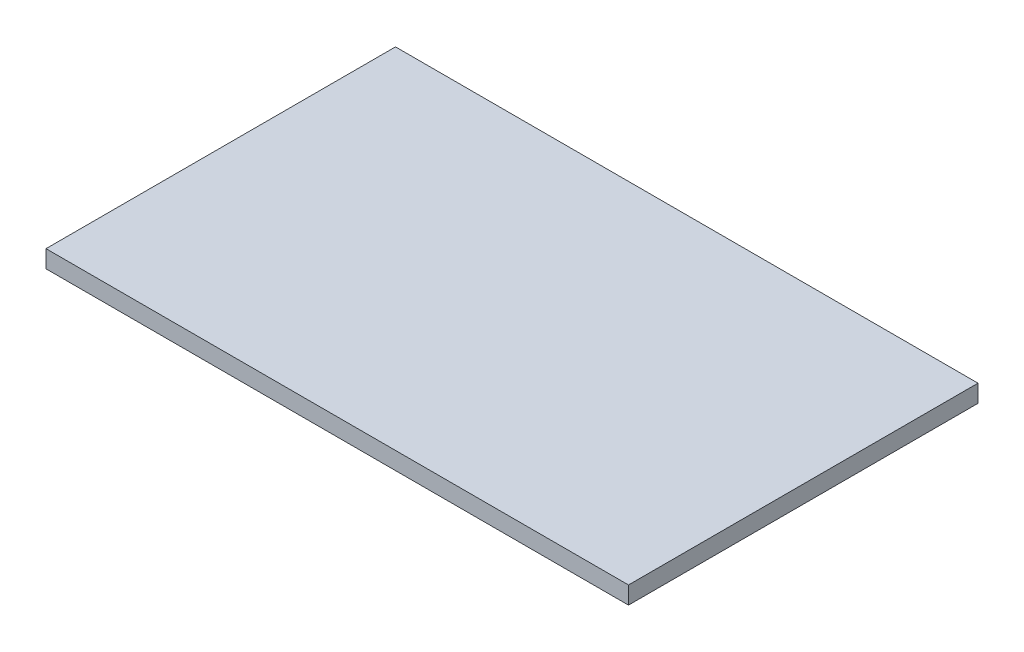
SolidWorks part; units mm, degrees
ref_plane "Front Plane" through (0, 0, 0) normal (0, 0, 1) x (1, 0, 0)
ref_plane "Top Plane" through (0, 0, 0) normal (0, 1, 0) x (1, 0, 0)
ref_plane "Right Plane" through (0, 0, 0) normal (1, 0, 0) x (0, 0, -1)
sketch "Sketch1" plane through (0, 0, 0) normal (0, 1, 0) x (1, 0, 0)
  line L0 (-55, 0) -> (55, 0) construction
  line L1 (-50, 30) -> (50, 30)
  line L2 (-50, 30) -> (-50, -30)
  line L3 (-50, -30) -> (50, -30)
  line L4 (50, 30) -> (50, -30)
  line L5 (0, -55) -> (0, 55) construction
  dimension "D1" = 100
  dimension "D2" = 60
  dimension "D3" = 30
  dimension "D4" = 50
extrude "Boss-Extrude1" add sketch "Sketch1" along normal blind 3
